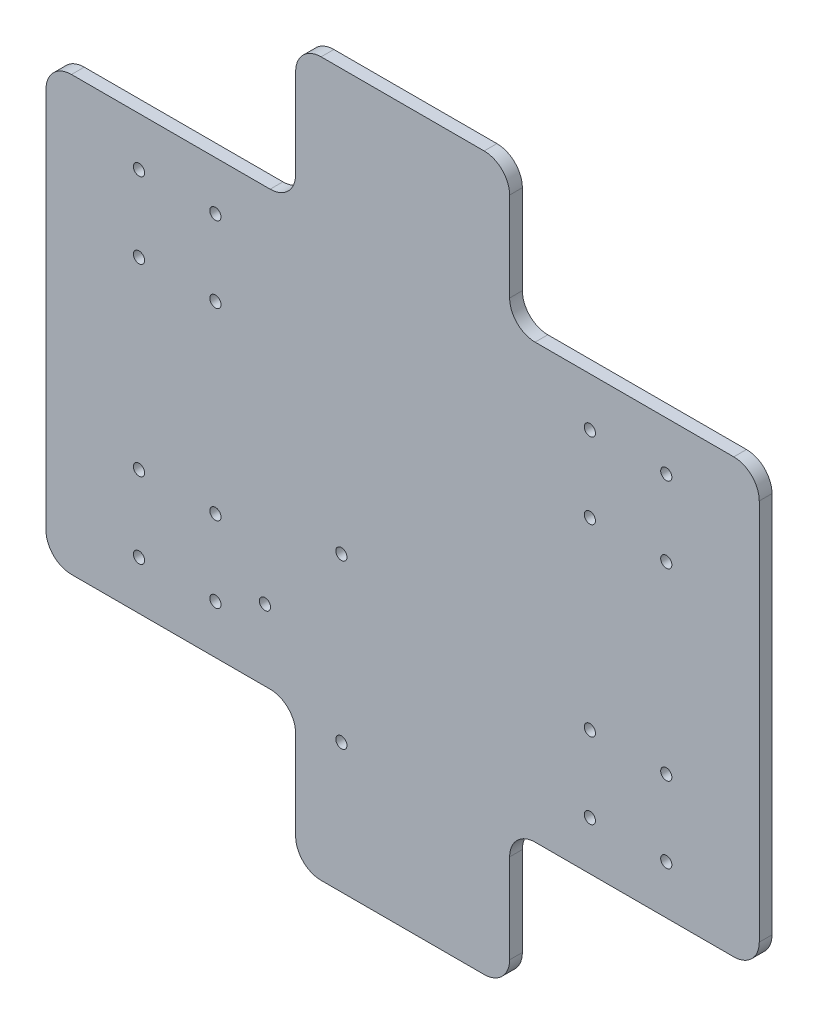
SolidWorks part; units mm, degrees
ref_plane "前视基准面" through (0, 0, 0) normal (0, 0, 1) x (1, 0, 0)
ref_plane "上视基准面" through (0, 0, 0) normal (0, 1, 0) x (1, 0, 0)
ref_plane "右视基准面" through (0, 0, 0) normal (1, 0, 0) x (0, 0, -1)
other "Configuration Table"
sketch "草图1" plane through (0, 0, 0) normal (0, 0, 1) x (1, 0, 0)
  line L5 (88.5, -78) -> (88.5, -50078) construction
  line L6 (-51.5, -163) -> (46.5, -163)
  line L7 (46.5, -218) -> (46.5, -163)
  line L9 (-51.5, -218) -> (46.5, -218)
  line L10 (88.5, -78) -> (50088.5, -78) construction
  line L11 (-51.5, -218) -> (-51.5, -163)
  line L12 (-51.5, 62) -> (46.5, 62)
  line L19 (-51.5, -218) -> (228.5, -218)
  line L20 (-51.5, -218) -> (-51.5, 62)
  line L21 (-51.5, 62) -> (228.5, 62)
  line L22 (228.5, -218) -> (228.5, 62)
  line L23 (-51.5, -218) -> (228.5, 62) construction
  line L24 (-51.5, 62) -> (228.5, -218) construction
  line L25 (228.5, -218) -> (130.5, -218)
  line L26 (228.5, -218) -> (228.5, -163)
  line L27 (228.5, -163) -> (130.5, -163)
  line L28 (130.5, -218) -> (130.5, -163)
  line L29 (46.5, 62) -> (46.5, 7)
  line L30 (-51.5, 7) -> (46.5, 7)
  line L31 (-51.5, 62) -> (-51.5, 7)
  line L32 (228.5, 7) -> (130.5, 7)
  line L33 (130.5, 62) -> (130.5, 7)
  line L34 (228.5, 62) -> (130.5, 62)
  line L35 (228.5, 62) -> (228.5, 7)
  circle A12 centre (192, -114.1) radius 2.2
  circle A13 centre (192, -143.9) radius 2.2
  circle A14 centre (162, -143.9) radius 2.2
  circle A15 centre (162, -114.1) radius 2.2
  circle A16 centre (162, -12.1) radius 2.2
  circle A17 centre (192, -12.1) radius 2.2
  circle A18 centre (192, -41.9) radius 2.2
  circle A19 centre (162, -41.9) radius 2.2
  circle A20 centre (-15, -143.9) radius 2.2
  circle A21 centre (15, -143.9) radius 2.2
  circle A22 centre (15, -114.1) radius 2.2
  circle A23 centre (-15, -114.1) radius 2.2
  circle A24 centre (-15, -41.9) radius 2.2
  circle A25 centre (15, -41.9) radius 2.2
  circle A26 centre (15, -12.1) radius 2.2
  circle A27 centre (-15, -12.1) radius 2.2
  point P0 (88.5, -78)
  point P3 (88.5, -78)
  dimension "D3" = 55
  dimension "D4" = 4.4
  dimension "D5" = 4.4
  dimension "D6" = 4.4
  dimension "D7" = 4.4
  dimension "D1" = 280
  dimension "D2" = 98
extrude "凸台-拉伸1" add sketch "草图1" along normal blind 5 contours L33 L21 L29 L30 L20 L6 L7 L19 L28 L27 L22 L32 A27 A26 A25 A24 A22 A20 A18 A16 A15 A14 A13 A12 A17 A19 A21 A23
fillet "圆角1" radius 10 12 edges at (130.5, 7, 2.5) (228.5, 7, 2.5) (228.5, -163, 2.5) (130.5, -163, 2.5) (-51.5, 7, 2.5) (46.5, 7, 2.5) (46.5, 62, 2.5) (130.5, 62, 2.5) (130.5, -218, 2.5) (46.5, -218, 2.5) (-51.5, -163, 2.5) (46.5, -163, 2.5)
sketch "草图2" plane through (0, 0, 0) normal (0, 0, -1) x (-1, 0, 0)
  circle A0 centre (-64.459, -103.0634) radius 2.2
  circle A1 centre (-34.459, -135.0634) radius 2.2
  circle A2 centre (-64.459, -167.0634) radius 2.2
  dimension "D1" = 4.4
  dimension "D2" = 4.4
  dimension "D3" = 4.4
extrude "切除-拉伸1" cut sketch "草图2" against normal up to next
